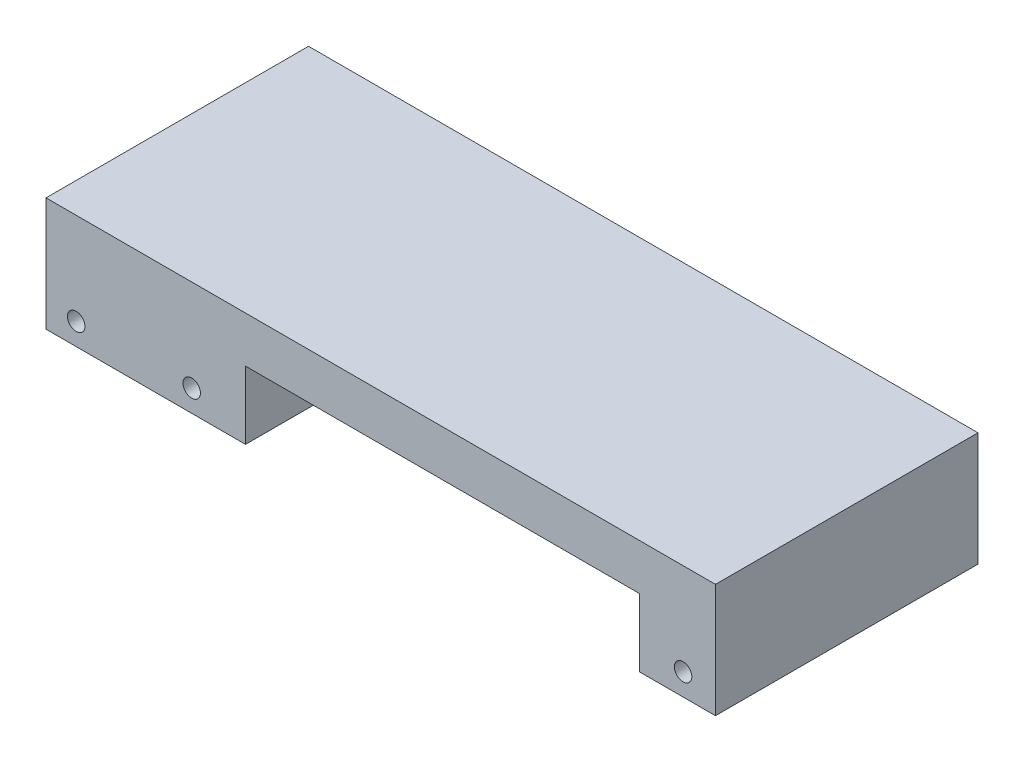
SolidWorks part; units mm, degrees
ref_plane "Alzado" through (0, 0, 0) normal (0, 0, 1) x (1, 0, 0)
ref_plane "Planta" through (0, 0, 0) normal (0, 1, 0) x (1, 0, 0)
ref_plane "Vista lateral" through (0, 0, 0) normal (1, 0, 0) x (0, 0, -1)
sketch "Croquis1" plane through (0, 0, 0) normal (0, 0, 1) x (1, 0, 0)
  line L1 (-38.25, -6.5) -> (38.25, -6.5)
  line L2 (-38.25, -6.5) -> (-38.25, 6.5)
  line L3 (-38.25, 6.5) -> (38.25, 6.5)
  line L4 (38.25, -6.5) -> (38.25, 6.5)
  line L5 (-38.25, -6.5) -> (38.25, 6.5) construction
  line L6 (-38.25, 6.5) -> (38.25, -6.5) construction
  line L7 (-15.45, -14.25) -> (29.55, -14.25)
  line L8 (-15.45, -14.25) -> (-15.45, 1.25)
  line L9 (-15.45, 1.25) -> (29.55, 1.25)
  line L10 (29.55, -14.25) -> (29.55, 1.25)
  line L11 (-15.45, -14.25) -> (29.55, 1.25) construction
  line L12 (-15.45, 1.25) -> (29.55, -14.25) construction
  circle A0 centre (-34.8, -4) radius 1
  circle A1 centre (-21.6, -4) radius 1
  circle A2 centre (34.55, -4) radius 1
  point P0 (0, 0)
  point P14 (7.05, -6.5)
  dimension "D1" = 2
  dimension "D2" = 76.5
  dimension "D3" = 69.35
  dimension "D4" = 13.2
  dimension "D5" = 3.45
  dimension "D6" = 13
  dimension "D7" = 4
  dimension "D8" = 45
  dimension "D9" = 5
  dimension "D10" = 15.5
extrude "Saliente-Extruir1" add sketch "Croquis1" along normal blind 30 contours L10 L1 L4 L3 L2 L8 L9 A2 A1 A0
